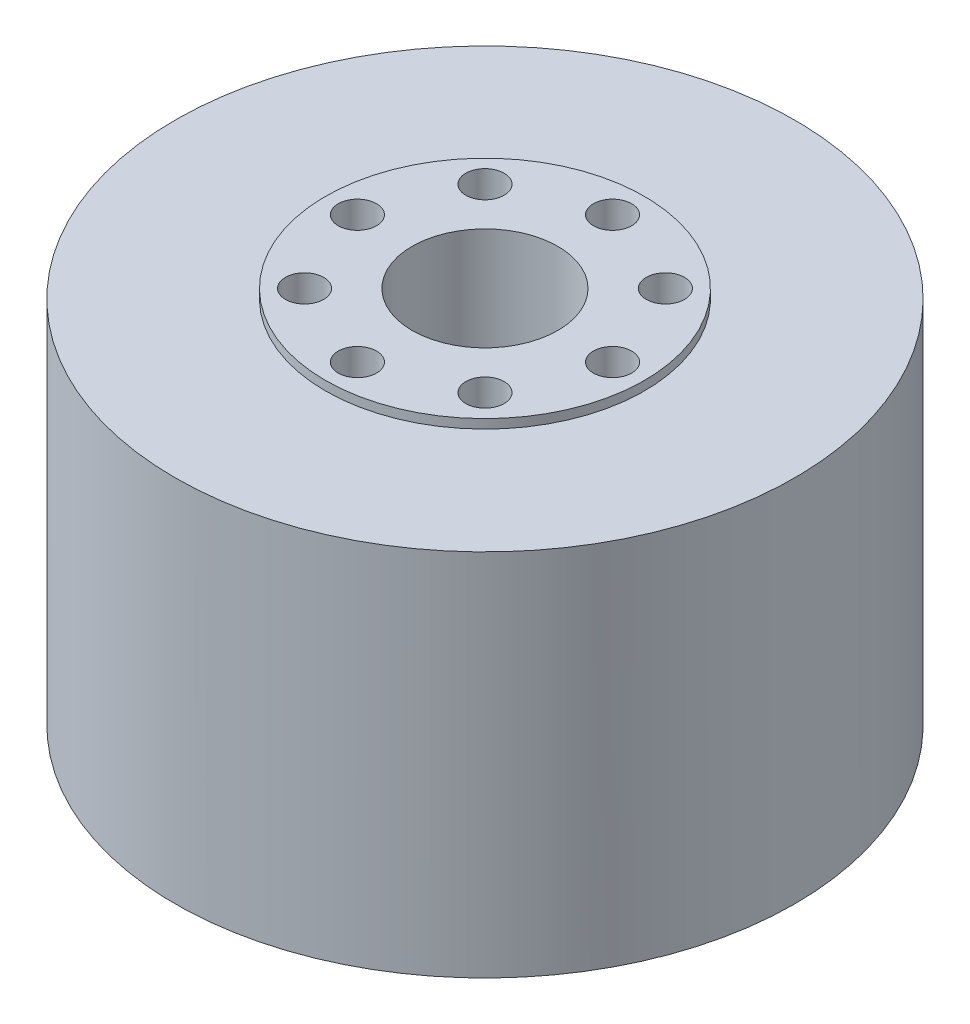
SolidWorks part; units mm, degrees
material "灰铸铁"
ref_plane "前视基准面" through (0, 0, 0) normal (0, 0, 1) x (1, 0, 0)
ref_plane "上视基准面" through (0, 0, 0) normal (0, 1, 0) x (1, 0, 0)
ref_plane "右视基准面" through (0, 0, 0) normal (1, 0, 0) x (0, 0, -1)
sketch "草图1" plane through (0, 0, 0) normal (0, 1, 0) x (1, 0, 0)
  circle A0 centre (0, 0) radius 8
  circle A1 centre (0, 0) radius 34
  dimension "D1" = 16
  dimension "D2" = 68
extrude "凸台-拉伸1" add sketch "草图1" along normal blind 40.5
ref_plane "基准面1" through (0, 40.5, 0) normal (0, 1, 0) x (1, 0, 0)
sketch "草图2" plane through (0, 40.5, 0) normal (0, 1, 0) x (1, 0, 0)
  circle A0 centre (0, 0) radius 8
  circle A1 centre (0, 0) radius 17.5
  dimension "D1" = 16
  dimension "D2" = 35
extrude "凸台-拉伸2" add sketch "草图2" along normal blind 1
ref_plane "基准面2" through (0, 41.5, 0) normal (0, 1, 0) x (1, 0, 0)
sketch "草图3" plane through (0, 41.5, 0) normal (0, 1, 0) x (1, 0, 0)
  circle A0 centre (0, 0) radius 14 construction
  circle A1 centre (14, 0) radius 2.1
  circle A2 centre (9.8995, -9.8995) radius 2.1
  circle A3 centre (0, -14) radius 2.1
  circle A4 centre (-9.8995, -9.8995) radius 2.1
  circle A5 centre (-14, 0) radius 2.1
  circle A6 centre (-9.8995, 9.8995) radius 2.1
  circle A7 centre (0, 14) radius 2.1
  circle A8 centre (9.8995, 9.8995) radius 2.1
  point P22 (0, 0)
  dimension "D1" = 28
  dimension "D2" = 4.2
  dimension "D3" = 8
extrude "切除-拉伸1" cut sketch "草图3" against normal blind 5
ref_plane "基准面3" through (0, 0, 0) normal (0, -1, 0) x (-1, 0, 0)
sketch "草图4" plane through (0, 0, 0) normal (0, -1, 0) x (-1, 0, 0)
  line L0 (28.8444, 18) -> (28.8444, -18)
  circle A0 centre (0, 0) radius 34 construction
  circle A1 centre (0, 0) radius 34
  dimension "D1" = 36
extrude "切除-拉伸2" cut sketch "草图4" against normal blind 8 contours L0 A1
sketch "草图5" plane through (0, 0, 0) normal (0, -1, 0) x (-1, 0, 0)
  line L0 (15, 25.9808) -> (15, -25.9808) construction
  line L1 (15, 25.9808) -> (-30, 0) construction
  line L2 (-30, 0) -> (15, -25.9808) construction
  circle A0 centre (0, 0) radius 30 construction
  circle A1 centre (-30, 0) radius 2.1
  circle A2 centre (15, 25.9808) radius 2.1
  circle A3 centre (15, -25.9808) radius 2.1
  dimension "D1" = 60
  dimension "D2" = 4.2
  dimension "D3" = 4.2
  dimension "D4" = 4.2
extrude "切除-拉伸3" cut sketch "草图5" against normal blind 5
